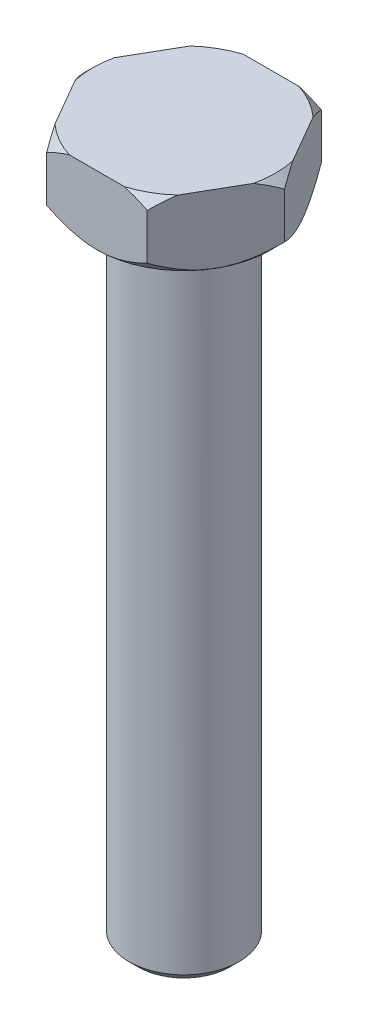
SolidWorks part; units mm, degrees
ref_plane "Спереди" through (0, 0, 0) normal (0, 0, 1) x (1, 0, 0)
ref_plane "Сверху" through (0, 0, 0) normal (0, 1, 0) x (1, 0, 0)
ref_plane "Справа" through (0, 0, 0) normal (1, 0, 0) x (0, 0, -1)
sketch "Эскиз1" plane through (0, 0, 0) normal (0, 1, 0) x (1, 0, 0)
  line L0 (-5.4848, 9.5) -> (5.4848, 9.5)
  line L1 (5.4848, 9.5) -> (10.9697, 0)
  line L2 (10.9697, 0) -> (5.4848, -9.5)
  line L3 (5.4848, -9.5) -> (-5.4848, -9.5)
  line L4 (-5.4848, -9.5) -> (-10.9697, 0)
  line L5 (-10.9697, 0) -> (-5.4848, 9.5)
  dimension "D5" = 9.5
  dimension "D2" = 120
  dimension "D3" = 120
  dimension "D4" = 120
  dimension "D6" = 9.5
  dimension "D7" = 9.5
  dimension "D8" = 9.5
  dimension "D9" = 9.5
  dimension "D10" = 120
  dimension "D11" = 9.5
extrude "Вытянуть1" add sketch "Эскиз1" against normal blind 7.5
sketch "Эскиз5" plane through (0, -7.5, 0) normal (0, -1, 0) x (1, 0, 0)
  circle A0 centre (0, 0) radius 6
  dimension "D1" = 12
extrude "Вытянуть2" add sketch "Эскиз5" along normal blind 70
chamfer "Фаска1" distance 1 angle 45 1 edges at (0, -77.5, -6)
ref_axis "Ось1" through (0, -7.5, 0) along (0, -1, 0)
ref_plane "Плоскость1" through (0, 0, 0) normal (0, 0, 1) x (1, 0, 0)
sketch "Эскиз4" plane through (0, 0, 0) normal (0, 0, 1) x (1, 0, 0)
  line L0 (-10.9697, -1) -> (-9.9697, 0)
  line L1 (-10.9697, -7.5) -> (-10.9697, 0) construction
  line L2 (-10.9697, 0) -> (-5.4848, 0) construction
  line L3 (-9.9697, 0) -> (-10.9697, 0)
  line L4 (-10.9697, 0) -> (-10.9697, -1)
  line L5 (-10.9697, -6) -> (-9.4697, -7.5)
  line L6 (-10.9697, -7.5) -> (-5.4848, -7.5) construction
  line L7 (-9.4697, -7.5) -> (-10.9697, -7.5)
  line L8 (-10.9697, -7.5) -> (-10.9697, -6)
  dimension "D1" = 1
  dimension "D2" = 1
  dimension "D3" = 1.5
  dimension "D4" = 1.5
revolve "Вырез-Повернуть1" cut sketch "Эскиз4" angle 360 about axis through (0, -7.5, 0) along (0, -1, 0)
